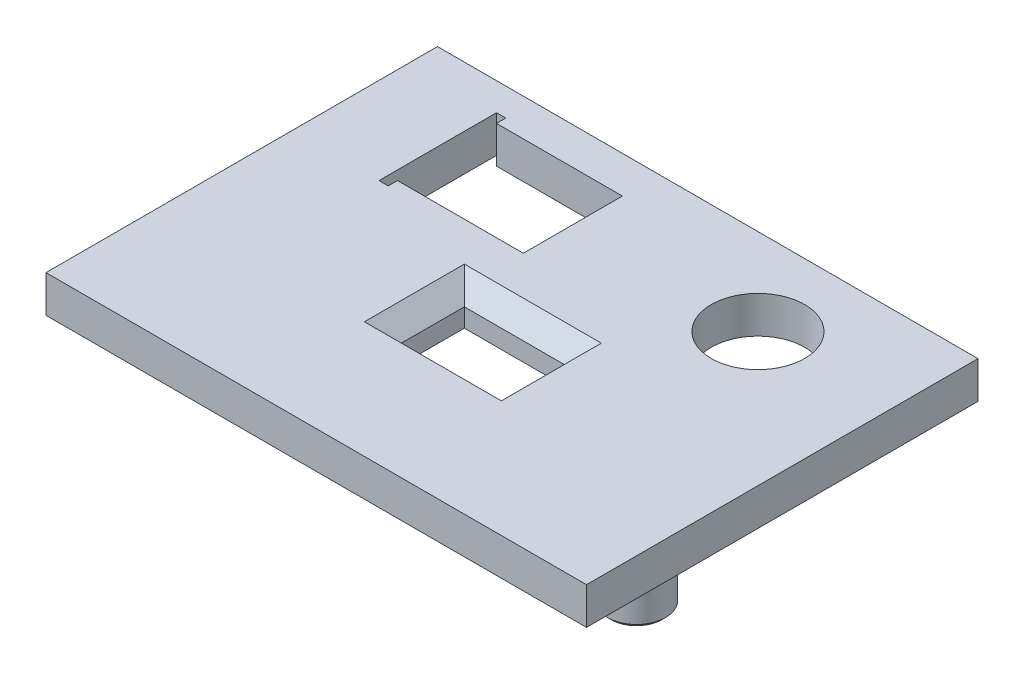
SolidWorks part; units mm, degrees
ref_plane "Front Plane" through (0, 0, 0) normal (0, 0, 1) x (1, 0, 0)
ref_plane "Top Plane" through (0, 0, 0) normal (0, 1, 0) x (1, 0, 0)
ref_plane "Right Plane" through (0, 0, 0) normal (1, 0, 0) x (0, 0, -1)
sketch "Parts" plane through (0, 0, 0) normal (0, 1, 0) x (1, 0, 0)
  line L0 (-9.9, 2.7) -> (-7.9, 2.7) construction
  line L1 (-7.9, 5.4) -> (7.9, 5.4) construction
  line L2 (-7.9, 5.4) -> (-7.9, 2.7) construction
  line L3 (-7.9, -5.4) -> (7.9, -5.4) construction
  line L4 (7.9, 5.4) -> (7.9, 2.7) construction
  line L5 (-7.9, 5.4) -> (7.9, -5.4) construction
  line L6 (-7.9, -5.4) -> (7.9, 5.4) construction
  line L7 (-9.9, -2.7) -> (-7.9, -2.7) construction
  line L8 (9.9, 2.7) -> (7.9, 2.7) construction
  line L9 (9.9, -2.7) -> (7.9, -2.7) construction
  line L10 (-7.9, -2.7) -> (-7.9, -5.4) construction
  line L11 (7.9, -2.7) -> (7.9, -5.4) construction
  line L12 (-9.9125, 9.075) -> (9.9125, 9.075) construction
  line L13 (-2.2, 2.8) -> (2.2, 2.8) construction
  line L14 (-2.2, 2.8) -> (-2.2, 0.4) construction
  line L15 (-2.2, 0.4) -> (2.2, 0.4) construction
  line L16 (2.2, 2.8) -> (2.2, 0.4) construction
  line L17 (-2.2, 2.8) -> (2.2, 0.4) construction
  line L18 (-2.2, 0.4) -> (2.2, 2.8) construction
  line L19 (-9.9125, 11.75) -> (-2.6125, 11.75) construction
  line L21 (-9.9125, 6.4) -> (-2.6125, 6.4) construction
  line L22 (-2.6125, 11.75) -> (-2.6125, 6.4) construction
  line L23 (-9.9125, 11.75) -> (-2.6125, 6.4) construction
  line L24 (-9.9125, 6.4) -> (-2.6125, 11.75) construction
  line L26 (-9.9125, 6.4) -> (-9.9125, 11.75) construction
  line L29 (-2.6125, 11.75) -> (1.3875, 11.75) construction
  line L31 (-2.6125, 6.4) -> (1.3875, 6.4) construction
  line L32 (1.3875, 11.75) -> (1.3875, 6.4) construction
  line L33 (-14.6, -7.4) -> (14.6, -7.4)
  line L34 (-14.6, -7.4) -> (-14.6, 13.75)
  line L35 (-14.6, 13.75) -> (14.6, 13.75)
  line L36 (14.6, -7.4) -> (14.6, 13.75)
  line L37 (0, 9.075) -> (0, 5.4) construction
  line L38 (-2.6125, 11.75) -> (-2.6125, 12.25) construction
  line L39 (-2.6125, 12.25) -> (1.3875, 12.25) construction
  line L40 (1.3875, 12.25) -> (1.3875, 11.75) construction
  line L41 (-2.6125, 6.4) -> (-2.6125, 5.9) construction
  line L42 (-2.6125, 5.9) -> (1.3875, 5.9) construction
  line L43 (1.3875, 5.9) -> (1.3875, 6.4) construction
  line L44 (-12.6, 0) -> (-14.6, 0) construction
  line L45 (12.6, 0) -> (14.6, 0) construction
  line L46 (-9.4125, 11.75) -> (-9.4125, 12.25) construction
  line L47 (-9.4125, 12.25) -> (-9.9125, 12.25) construction
  line L48 (-9.9125, 12.25) -> (-9.9125, 11.75) construction
  line L49 (-9.9125, 6.4) -> (-9.9125, 5.9) construction
  line L50 (-9.9125, 5.9) -> (-9.4125, 5.9) construction
  line L51 (-9.4125, 5.9) -> (-9.4125, 6.4) construction
  arc A0 (-9.9, 2.7) -> (-9.9, -2.7) centre (-9.9, 0) ccw construction
  arc A1 (9.9, -2.7) -> (9.9, 2.7) centre (9.9, 0) ccw construction
  circle A2 centre (-9.9, 0) radius 1.575 construction
  circle A3 centre (9.9, 0) radius 1.575 construction
  circle A4 centre (7.3875, 9.075) radius 2.525 construction
  point P0 (0, 0)
  point P16 (0, 1.6)
  point P23 (-6.2625, 9.075)
  dimension "D3" = 5.4
  dimension "D4" = 5.4
  dimension "D5" = 3.15
  dimension "D6" = 3.15
  dimension "D14" = 5.05
  dimension "D1" = 10.8
  dimension "D2" = 15.8
  dimension "D7" = 2.4
  dimension "D8" = 4.4
  dimension "D9" = 5.8
  dimension "D10" = 7.3
  dimension "D11" = 4
  dimension "D12" = 5.35
  dimension "D13" = 1
  dimension "D15" = 2
  dimension "D16" = 2
  dimension "D17" = 2
  dimension "D18" = 6
  dimension "D19" = 0.5
  dimension "D20" = 0.5
  dimension "D21" = 2
  dimension "D22" = 0.5
  dimension "D23" = 0.5
extrude "Main Face" add sketch "Parts" against normal blind 2
sketch "Sketch3" plane through (0, 0, 0) normal (0, 1, 0) x (1, 0, 0)
  line L0 (-2.6125, 11.75) -> (-2.6125, 6.4) construction
  line L1 (-9.9125, 11.75) -> (-2.6125, 11.75) construction
  line L2 (-9.9125, 6.4) -> (-9.9125, 11.75) construction
  line L3 (-9.9125, 6.4) -> (-2.6125, 6.4) construction
  line L4 (-2.6125, 11.75) -> (-2.6125, 6.4)
  line L5 (-9.4125, 11.75) -> (-2.6125, 11.75)
  line L6 (-9.9125, 6.4) -> (-9.9125, 11.75)
  line L7 (-9.4125, 6.4) -> (-2.6125, 6.4)
  line L8 (-9.9125, 6.4) -> (-9.9125, 5.9) construction
  line L9 (-9.4125, 5.9) -> (-9.4125, 6.4) construction
  line L10 (-9.9125, 5.9) -> (-9.4125, 5.9) construction
  line L11 (-9.4125, 11.75) -> (-9.4125, 12.25) construction
  line L12 (-9.4125, 12.25) -> (-9.9125, 12.25) construction
  line L13 (-9.9125, 12.25) -> (-9.9125, 11.75) construction
  line L14 (-9.9125, 6.4) -> (-9.9125, 5.9)
  line L15 (-9.4125, 5.9) -> (-9.4125, 6.4)
  line L16 (-9.9125, 5.9) -> (-9.4125, 5.9)
  line L17 (-9.4125, 11.75) -> (-9.4125, 12.25)
  line L18 (-9.4125, 12.25) -> (-9.9125, 12.25)
  line L19 (-9.9125, 12.25) -> (-9.9125, 11.75)
  circle A0 centre (7.3875, 9.075) radius 2.525 construction
  circle A1 centre (7.3875, 9.075) radius 2.525
extrude "IR Cut" cut sketch "Sketch3" against normal blind 2
sketch "Sketch5" plane through (0, -2, 0) normal (0, -1, 0) x (1, 0, 0)
  line L0 (-2.6125, -11.75) -> (-2.6125, -6.4) construction
  line L2 (1.3875, -11.75) -> (1.3875, -6.4) construction
  line L4 (-2.6125, -11.75) -> (-2.6125, -6.4)
  line L6 (1.3875, -11.75) -> (1.3875, -6.4)
  line L8 (1.3875, -5.9) -> (1.3875, -6.4) construction
  line L9 (-2.6125, -5.9) -> (1.3875, -5.9) construction
  line L10 (-2.6125, -6.4) -> (-2.6125, -5.9) construction
  line L11 (1.3875, -12.25) -> (1.3875, -11.75) construction
  line L12 (-2.6125, -12.25) -> (1.3875, -12.25) construction
  line L13 (-2.6125, -11.75) -> (-2.6125, -12.25) construction
  line L14 (1.3875, -5.9) -> (1.3875, -6.4)
  line L15 (-2.6125, -5.9) -> (1.3875, -5.9)
  line L16 (-2.6125, -6.4) -> (-2.6125, -5.9)
  line L17 (1.3875, -12.25) -> (1.3875, -11.75)
  line L18 (-2.6125, -12.25) -> (1.3875, -12.25)
  line L19 (-2.6125, -11.75) -> (-2.6125, -12.25)
extrude "TSOP Groove" cut sketch "Sketch5" against normal blind 1.5
sketch "Sketch4" plane through (0, 0, 0) normal (0, 1, 0) x (1, 0, 0)
  line L14 (-2.7, -0.1) -> (2.7, -0.1)
  line L15 (2.7, -0.1) -> (2.7, 3.3)
  line L16 (2.7, 3.3) -> (-2.7, 3.3)
  line L17 (-2.7, 3.3) -> (-2.7, -0.1)
  line L18 (-2.7, -0.1) -> (2.7, -0.1)
  line L19 (2.7, -0.1) -> (2.7, 3.3)
  line L20 (2.7, 3.3) -> (-2.7, 3.3)
  line L21 (-2.7, 3.3) -> (-2.7, -0.1)
  dimension "D1" = 0.5
extrude "TOF Cut" cut sketch "Sketch4" against normal blind 2
sketch "Sketch6" plane through (0, -2, 0) normal (0, -1, 0) x (1, 0, 0)
  circle A0 centre (-9.9, 0) radius 1.575 construction
  circle A1 centre (9.9, 0) radius 1.575 construction
  circle A6 centre (-9.9, 0) radius 1.575
  circle A9 centre (9.9, 0) radius 1.575
extrude "Shafts" add sketch "Sketch6" along normal blind 5
chamfer "Chamfer1" distance 0.2 angle 45 2 edges at (9.9, -7, -1.575) (-9.9, -7, -1.575)
sketch "Sketch7" plane through (0, -2, 0) normal (0, -1, 0) x (1, 0, 0)
  line L1 (-7.5, 4.9) -> (7.5, 4.9)
  line L2 (-7.5, 4.9) -> (-7.5, 1.4)
  line L3 (-7.5, 1.4) -> (7.5, 1.4)
  line L4 (7.5, 4.9) -> (7.5, 1.4)
  line L5 (-7.5, 4.9) -> (7.5, 1.4) construction
  line L6 (-7.5, 1.4) -> (7.5, 4.9) construction
  line L7 (-7.9, 5.4) -> (7.9, 5.4) construction
  point P0 (0, 3.15)
  dimension "D1" = 3.5
  dimension "D2" = 15
  dimension "D3" = 0.5
extrude "PinSlots" cut sketch "Sketch7" against normal blind 1
chamfer "ToFWindow" distance 1 angle 45 4 edges at (2.7, 0, -1.6) (0, 0, 0.1) (-2.7, 0, -1.6) (0, 0, -3.3)
